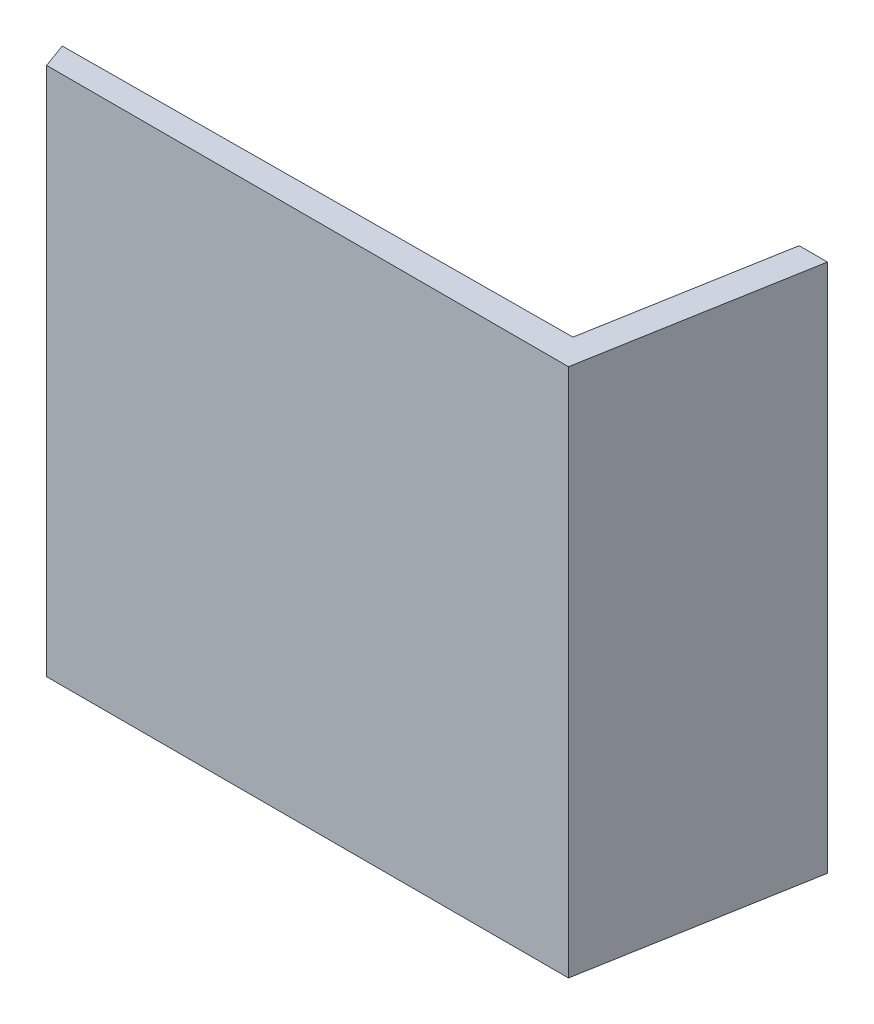
SolidWorks part; units mm, degrees
material "Custom Plastic"
ref_plane "Front Plane" through (0, 0, 0) normal (1, 0, 0) x (0, 1, 0)
ref_plane "Top Plane" through (0, 0, 0) normal (0, 0, 1) x (0, 1, 0)
ref_plane "Right Plane" through (0, 0, 0) normal (0, 1, 0) x (-1, 0, 0)
sketch "Sketch1" plane through (0, 0, 0) normal (0, 1, 0) x (-1, 0, 0)
  line L0 (-72.4911, -52.5) -> (42.5089, -52.5) construction
  line L1 (42.5089, -52.5) -> (28.1321, -13) construction
  line L2 (28.1321, -13) -> (-65.5261, -13)
  line L3 (-65.5261, -13) -> (-72.4911, -52.5)
  line L4 (29.7391, -17.4151) -> (-61.3306, -18)
  line L5 (-61.3306, -18) -> (-67.4139, -52.5)
  line L6 (-72.4911, -52.5) -> (-67.4139, -52.5)
  line L7 (28.1321, -13) -> (29.7391, -17.4151)
  arc A0 (-18.3644, -13) -> (18.3644, -13) centre (0, 0) ccw construction
  point P8 (-18.3644, -13)
  dimension "D1" = 45
  dimension "D2" = 115
  dimension "D3" = 13
  dimension "D4" = 80
  dimension "D5" = 70
  dimension "D6" = 13
  dimension "D7" = 28.1321
  dimension "D8" = 39.5
  dimension "D10" = 5
  dimension "D9" = 0.368
  dimension "D11" = 91.0697
extrude "Boss-Extrude1" add sketch "Sketch1" along normal blind 95
